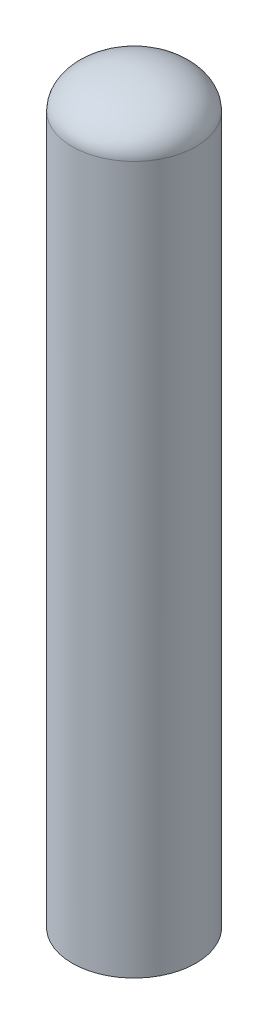
SolidWorks part; units mm, degrees
ref_plane "Front Plane" through (0, 0, 0) normal (0, 0, 1) x (1, 0, 0)
ref_plane "Top Plane" through (0, 0, 0) normal (0, 1, 0) x (1, 0, 0)
ref_plane "Right Plane" through (0, 0, 0) normal (1, 0, 0) x (0, 0, -1)
sketch "Sketch1" plane through (0, 0, 0) normal (0, 1, 0) x (1, 0, 0)
  circle A0 centre (0, 0) radius 44.45
  circle A1 centre (0, 0) radius 38.1
  dimension "D1" = 88.9
  dimension "D2" = 76.2
extrude "Boss-Extrude1" add sketch "Sketch1" along normal blind 508
sketch "Sketch3" plane through (0, 0, 0) normal (0, 0, 1) x (1, 0, 0)
  line L2 (38.1, 508) -> (-38.1, 508) construction
  line L3 (0, 527.05) -> (0, 533.4)
  line L4 (38.1, 508) -> (44.45, 508)
  line L7 (44.45, 0) -> (44.45, 508) construction
  ellipse E0 centre (0, 508) end of major axis (-44.45, 508) minor radius 25.4 (0, 533.4) -> (44.45, 508) cw
  spline S1 degree 3 poles (0, 527.05) (2.7052, 526.9626) (8.1643, 526.4983) (15.911, 524.9774) (22.9197, 522.7193) (28.8448, 519.8721) (33.4074, 516.658) (36.4169, 513.3874) (37.6558, 510.9398) (38.0661, 509.2139) (38.1132, 508.4101) (38.1, 508) knots 0 0 0 0 0.19635 0.392699 0.589049 0.785398 0.981748 1.178097 1.374447 1.472622 1.570796 1.570796 1.570796 1.570796
  point P0 (0, 508)
  point P1 (0, 0)
  point P4 (-0.9791, 532.0321)
  point P5 (0, 0)
  point P6 (-3.5343, 527.05)
  point P9 (51.2459, 509.7299)
  point P17 (0, 0)
  point P18 (0, 0)
  point P19 (52.0696, 508)
  point P20 (0, 0)
  point P24 (0.9601, 533.0192)
  point P25 (0, 0)
  point P27 (-7.229, 527.05)
  point P28 (0.3001, 527.05)
  point P29 (0, 0)
  dimension "D2" = 25.4
  dimension "D4" = 19.05
revolve "Revolve1" add sketch "Sketch3" angle 360 about L3
combine bodies "Combine1" operation type add bodies to combine 102 101
